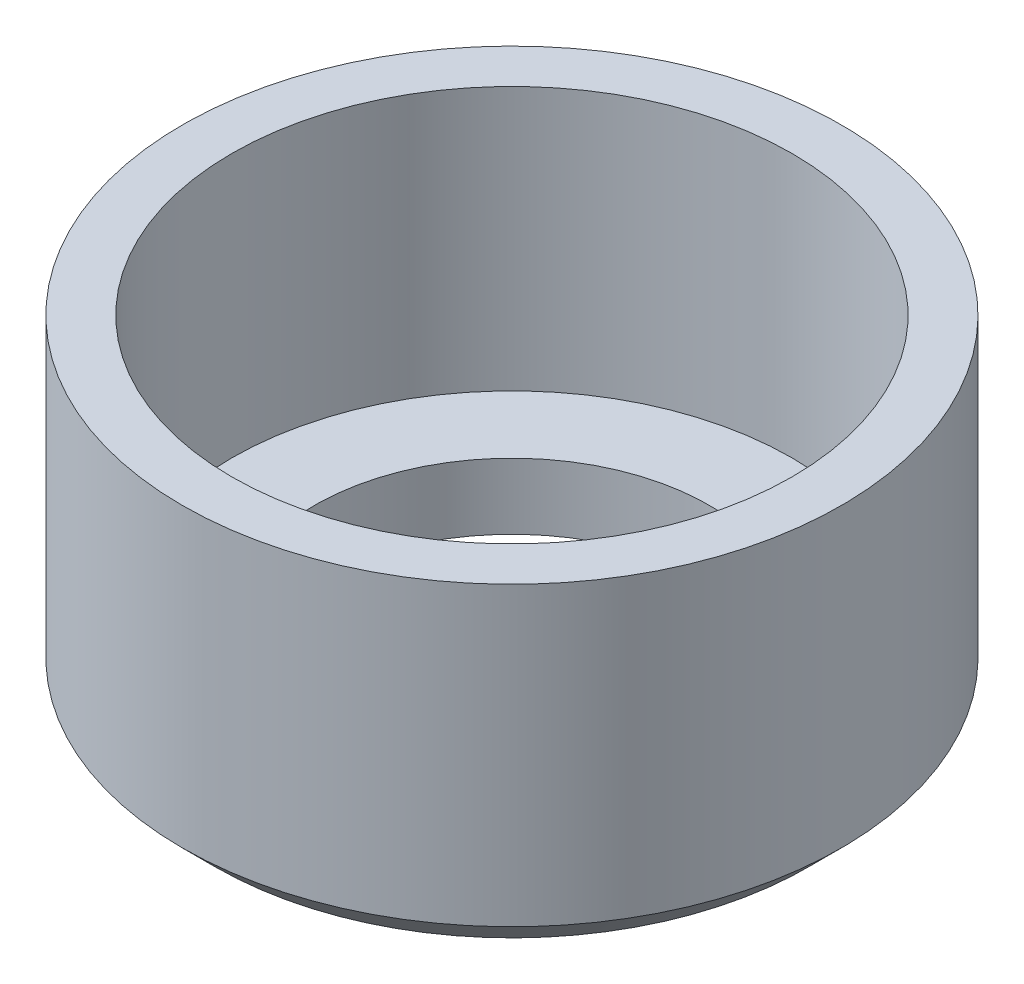
SolidWorks part; units mm, degrees
ref_plane "Front Plane" through (0, 0, 0) normal (0, 0, 1) x (1, 0, 0)
ref_plane "Top Plane" through (0, 0, 0) normal (0, 1, 0) x (1, 0, 0)
ref_plane "Right Plane" through (0, 0, 0) normal (1, 0, 0) x (0, 0, -1)
sketch "Sketch2" plane through (0, 0, 0) normal (0, 1, 0) x (1, 0, 0)
  circle A0 centre (0, 0) radius 6
  circle A1 centre (0, 0) radius 10
  dimension "D1" = 12
  dimension "D2" = 20
extrude "Boss-Extrude1" add sketch "Sketch2" along normal blind 10
sketch "Sketch3" plane through (0, 10, 0) normal (0, 1, 0) x (1, 0, 0)
  circle A0 centre (0, 0) radius 8.5
  dimension "D1" = 17
extrude "Cut-Extrude1" cut sketch "Sketch3" against normal blind 8 contours A0
chamfer "Chamfer1" distance 1 angle 45 1 edges at (0, 0, 10)
